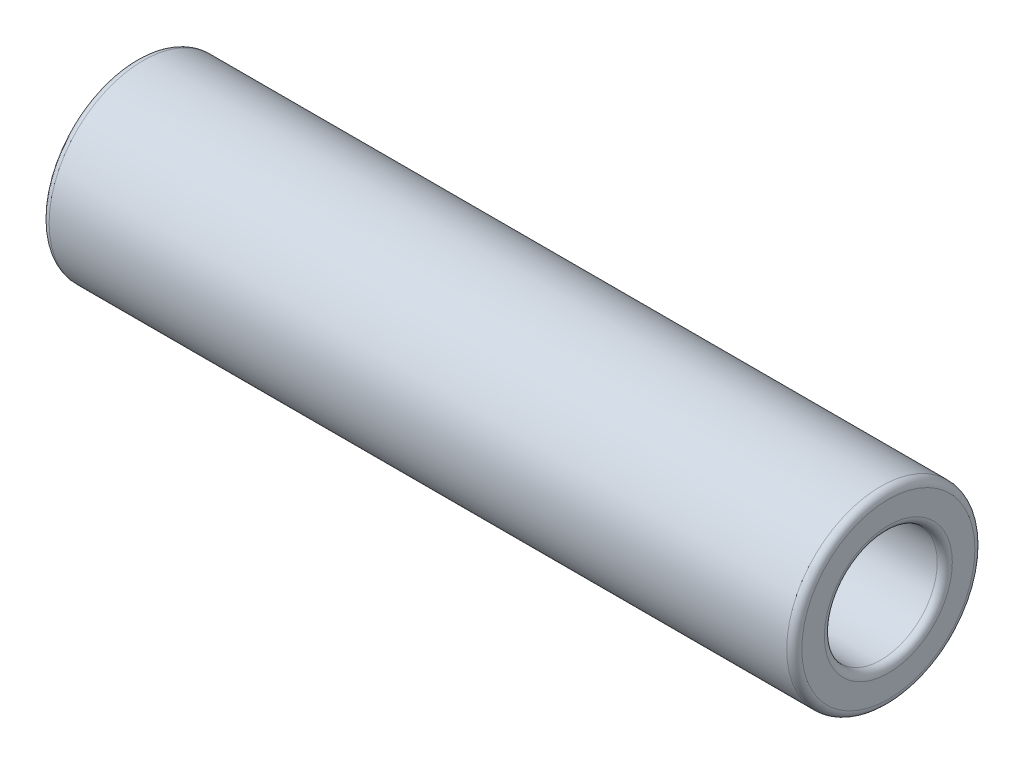
SolidWorks part; units mm, degrees
ref_plane "Front Plane" through (0, 0, 0) normal (0, 0, 1) x (1, 0, 0)
ref_plane "Top Plane" through (0, 0, 0) normal (0, 1, 0) x (1, 0, 0)
ref_plane "Right Plane" through (0, 0, 0) normal (1, 0, 0) x (0, 0, -1)
sketch "Sketch2" plane through (0, 0, 0) normal (1, 0, 0) x (0, 0, -1)
  circle A0 centre (0, 0) radius 6.25
  circle A1 centre (0, 0) radius 3.75
  dimension "D1" = 12.5
  dimension "D2" = 7.5
extrude "Boss-Extrude1" add sketch "Sketch2" along normal blind 50
fillet "Fillet1" radius 0.5 4 edges at (0, 0, -3.75) (0, 0, -6.25) (50, 0, -3.75) (50, 0, -6.25)
